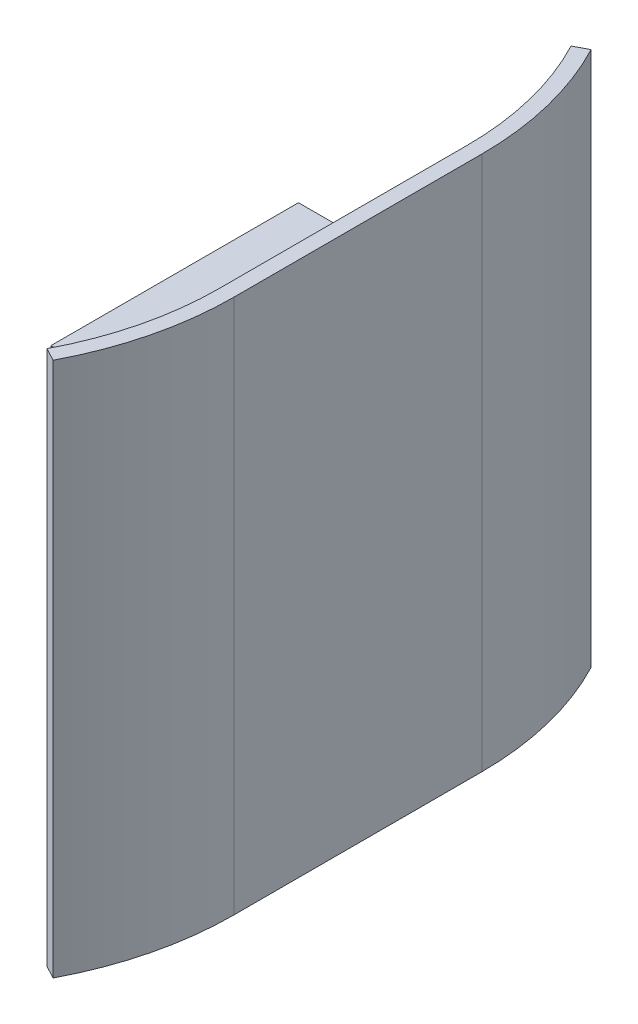
SolidWorks part; units mm, degrees
ref_plane "Ön Düzlem" through (0, 0, 0) normal (0, 0, 1) x (1, 0, 0)
ref_plane "Üst Düzlem" through (0, 0, 0) normal (0, 1, 0) x (1, 0, 0)
ref_plane "Sağ Düzlem" through (0, 0, 0) normal (1, 0, 0) x (0, 0, -1)
sketch "Çizim1" plane through (0, 0, 0) normal (0, 0, 1) x (1, 0, 0)
  line L1 (0, 0) -> (30, 0)
  line L2 (0, 0) -> (0, 50)
  line L3 (0, 50) -> (30, 50)
  line L4 (30, 0) -> (30, 50)
  dimension "D1" = 50
  dimension "D2" = 30
extrude "Ekstrüzyon-İnce1" add sketch "Çizim1" along normal blind 50 thin
sketch "Çizim2" plane through (-2, 0, 0) normal (-1, 0, 0) x (0, 0, 1)
  circle A0 centre (25, 25) radius 4
  circle A1 centre (33, 25) radius 2
  circle A2 centre (17, 25) radius 2
  circle A3 centre (25, 33) radius 2
  circle A4 centre (25, 17) radius 2
  dimension "D1" = 8
  dimension "D2" = 4
  dimension "D3" = 8
  dimension "D4" = 4
  dimension "D5" = 8
extrude "Kes-Ekstrüzyon1" cut sketch "Çizim2" against normal up to next
sketch "Çizim3" plane through (0, 52, 0) normal (0, 1, 0) x (1, 0, 0)
  line L0 (32, -50) -> (32, 0)
  line L1 (32, -50) -> (32, 0) construction
  line L2 (32, 0) -> (-2, 0) construction
  line L3 (32, -25) -> (25.1182, -25) construction
  arc A0 (32, 0) -> (25.1182, 27.9009) centre (-28, 0) ccw
  arc A1 (32, -50) -> (25.1182, -77.9009) centre (-28, -50) cw
  dimension "D1" = 60
extrude "Ekstrüzyon-İnce2" add sketch "Çizim3" against normal mid plane 54 thin
mirror "Aynalama1" about plane through (-28, 25, 50) normal (0, -1, 0) of "Ekstrüzyon-İnce2"
